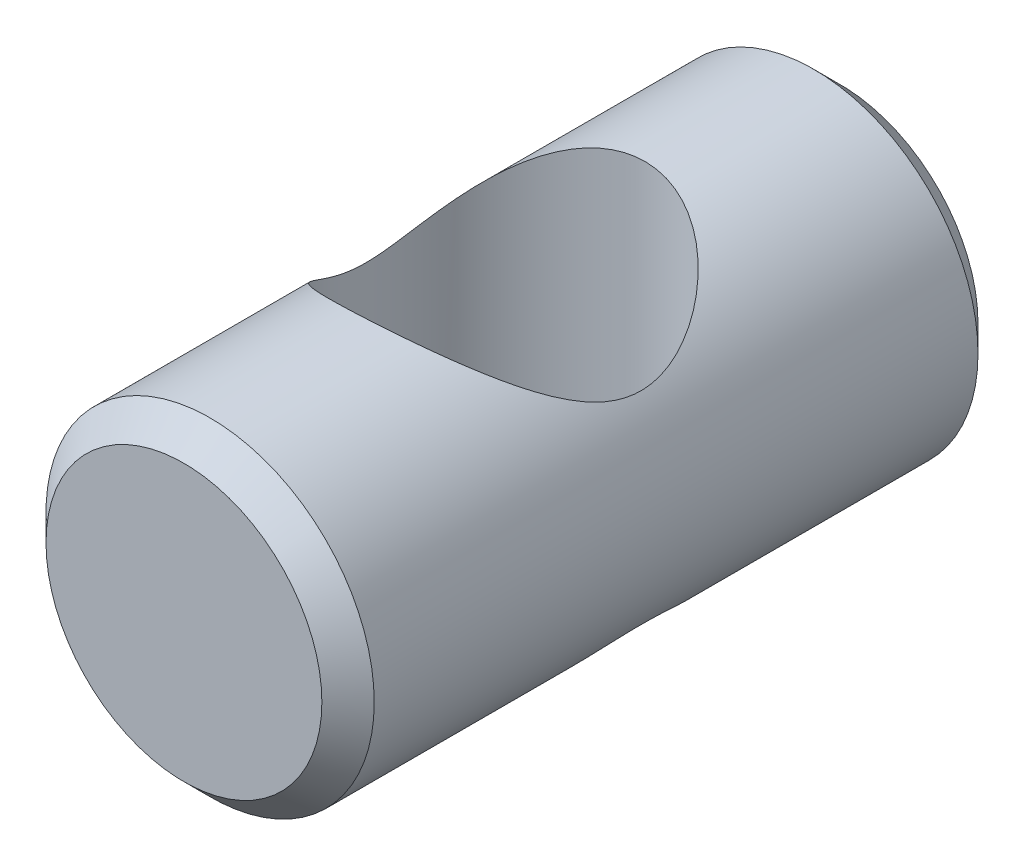
SolidWorks part; units mm, degrees
ref_plane "Front Plane" through (0, 0, 0) normal (0, 0, 1) x (1, 0, 0)
ref_plane "Top Plane" through (0, 0, 0) normal (0, 1, 0) x (1, 0, 0)
ref_plane "Right Plane" through (0, 0, 0) normal (1, 0, 0) x (0, 0, -1)
sketch "Sketch1" plane through (0, 0, 0) normal (0, 0, 1) x (1, 0, 0)
  circle A0 centre (0, 0) radius 4.765
  dimension "D1" = 9.53
extrude "Boss-Extrude1" add sketch "Sketch1" along normal mid plane 19.05
chamfer "Chamfer1" distance 0.76 angle 45 2 edges at (4.765, 0, -9.525) (4.765, 0, 9.525)
sketch "Sketch2" plane through (0, 0, 0) normal (0, 1, 0) x (1, 0, 0)
  circle A1 centre (-0.25, 0) radius 4
  point P2 (0, 0)
  point P3 (0, 0)
  dimension "D1" = 8
  dimension "D2" = 0.25
extrude "Cut-Extrude1" cut sketch "Sketch2" against normal through all both and the other way through all
